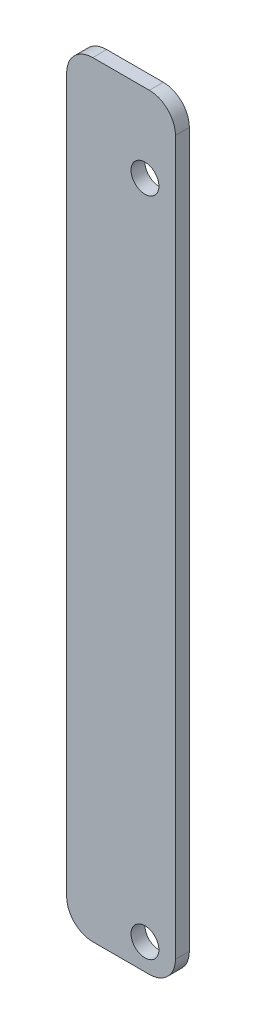
SolidWorks part; units mm, degrees
ref_plane "Front Plane" through (0, 0, 0) normal (0, 0, 1) x (1, 0, 0)
ref_plane "Top Plane" through (0, 0, 0) normal (0, 1, 0) x (1, 0, 0)
ref_plane "Right Plane" through (0, 0, 0) normal (1, 0, 0) x (0, 0, -1)
sketch "Sketch2" plane through (0, 0, 96.8383) normal (0, 0, 1) x (1, 0, 0)
  line L1 (-46.8525, 38.0188) -> (-59.3525, 38.0188)
  line L2 (-46.8525, 38.0188) -> (-46.8525, -49.9812)
  line L3 (-46.8525, -49.9812) -> (-59.3525, -49.9812)
  line L4 (-59.3525, 38.0188) -> (-59.3525, -49.9812)
  point P6 (-59.3525, -49.9812)
  point P9 (-59.3525, 38.0188)
  dimension "D1" = 12.5
  dimension "D2" = 88
extrude "Boss-Extrude1" add sketch "Sketch2" along normal blind 1.6
hole_wizard "Ø3.2 (3.2) Diameter Hole1" positions "Sketch4" profile "Sketch3" hole size "Ø3.2" standard "Ansi Metric"
sketch "Sketch4" plane through (0, 0, 98.4383) normal (0, 0, 1) x (1, 0, 0)
  line L0 (-59.3525, -49.9812) -> (-46.8525, -49.9812) construction
  line L1 (-59.3525, 38.0188) -> (-59.3525, -49.9812) construction
  line L2 (-46.8525, 38.0188) -> (-59.3525, 38.0188) construction
  point P0 (-50.3525, 29.0188)
  point P1 (-50.3525, -46.9812)
  dimension "D1" = 3
  dimension "D2" = 9
  dimension "D3" = 9
  dimension "D4" = 9
sketch "Sketch3" plane through (-50.3525, 29.0188, 98.4383) normal (1, 0, 0) x (0, -1, 0)
  line L0 (0, 0) -> (0, 2.5614)
  line L1 (0, 2.5614) -> (1.6, 1.6)
  line L2 (1.6, 1.6) -> (1.6, 0)
  line L5 (1.6, 0) -> (0, 0)
  line L10 (0, 2.5614) -> (-1.6, 1.6) construction
  line L11 (0, -6.35) -> (0, 107.95) construction
  dimension "Hole Dia." = 3.2
  dimension "Hole Depth" = 1.6
  dimension "Drill Angle" = 118
fillet "Fillet1" radius 3 4 edges at (-46.8525, 38.0188, 97.6383) (-59.3525, 38.0188, 97.6383) (-46.8525, -49.9812, 97.6383) (-59.3525, -49.9812, 97.6383)
